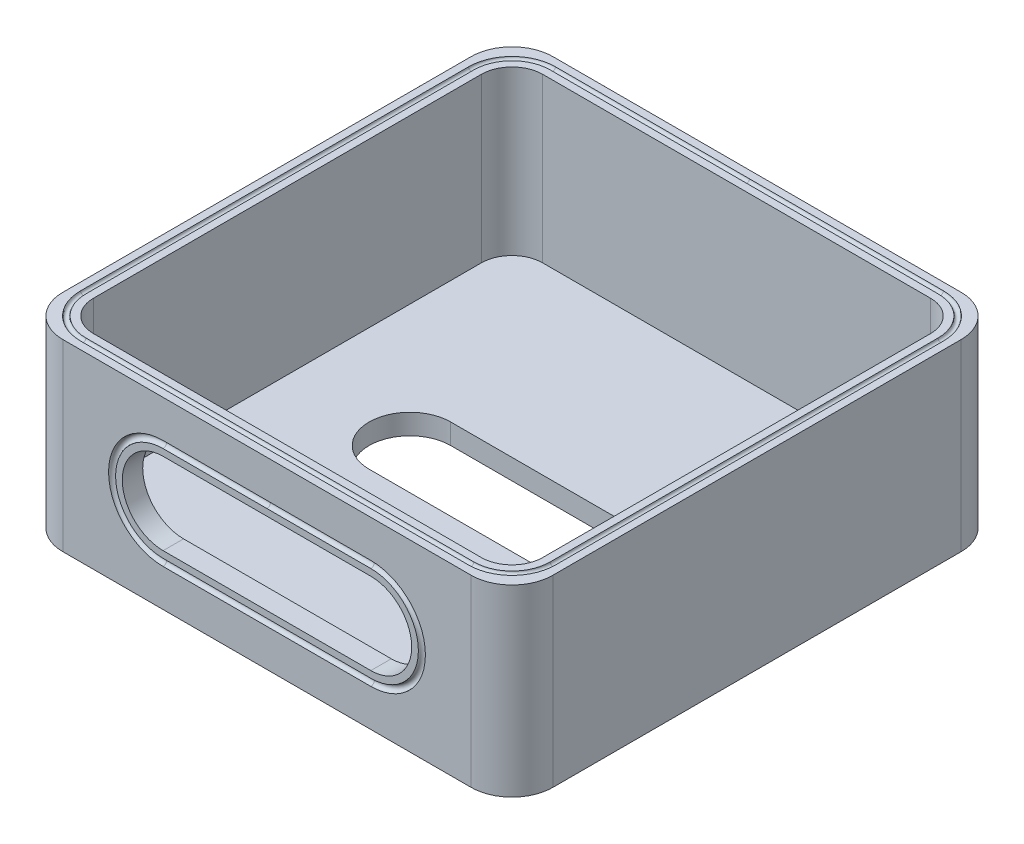
SolidWorks part; units mm, degrees
ref_plane "Front Plane" through (0, 0, 0) normal (0, 0, 1) x (1, 0, 0)
ref_plane "Top Plane" through (0, 0, 0) normal (0, 1, 0) x (1, 0, 0)
ref_plane "Right Plane" through (0, 0, 0) normal (1, 0, 0) x (0, 0, -1)
sketch "Sketch1" plane through (0, 0, 0) normal (0, 1, 0) x (1, 0, 0)
  line L0 (0, -152.4) -> (0, 152.4) construction
  line L1 (-152.4, -152.4) -> (152.4, -152.4)
  line L2 (-152.4, -152.4) -> (-152.4, 152.4)
  line L3 (-152.4, 152.4) -> (152.4, 152.4)
  line L4 (152.4, -152.4) -> (152.4, 152.4)
  line L5 (-152.4, -152.4) -> (152.4, 152.4) construction
  line L6 (-152.4, 152.4) -> (152.4, -152.4) construction
  line L7 (-152.4, 0) -> (152.4, 0) construction
  line L16 (0, -63.5) -> (0, 63.5) construction
  line L28 (-139.7, 139.7) -> (139.7, 139.7)
  line L29 (139.7, -139.7) -> (139.7, 139.7)
  line L30 (-139.7, -139.7) -> (139.7, -139.7)
  line L31 (-139.7, -139.7) -> (-139.7, 139.7)
  point P0 (0, 0)
  point P10 (0, 0)
  point P11 (0, 0)
  point P13 (-120.65, -184.15)
  point P26 (127, 190.5)
  point P27 (-127, 152.4)
  point P28 (-120.65, 184.15)
  dimension "12" = 304.8
  dimension "D2" = 304.8
  dimension "D6" = 12.7
extrude "Boss-Extrude1" add sketch "Sketch1" along normal blind 114.3
shell "Shell1" thickness 12.7
sketch "Sketch2" plane through (0, 0, 152.4) normal (0, 0, 1) x (1, 0, 0)
  line L0 (-64.6, 57.15) -> (64.6, 57.15) construction
  line L1 (-64.6, 82.55) -> (64.6, 82.55)
  line L2 (-64.6, 31.75) -> (64.6, 31.75)
  line L5 (-64.6, 88.9) -> (64.6, 88.9)
  line L6 (-64.6, 25.4) -> (64.6, 25.4)
  line L7 (0, 0) -> (0, 114.3) construction
  line L10 (-152.4, 114.3) -> (152.4, 114.3) construction
  arc A0 (-64.6, 82.55) -> (-64.6, 31.75) centre (-64.6, 57.15) ccw
  arc A1 (64.6, 31.75) -> (64.6, 82.55) centre (64.6, 57.15) ccw
  arc A2 (64.6, 25.4) -> (64.6, 88.9) centre (64.6, 57.15) ccw
  arc A3 (-64.6, 88.9) -> (-64.6, 25.4) centre (-64.6, 57.15) ccw
  point P2 (0, 57.15)
  point P16 (90, 57.15)
  point P17 (-90, 57.15)
  dimension "D1" = 50.8
  dimension "D2" = 180
  dimension "D3" = 6.35
extrude "Cut-Extrude1" cut sketch "Sketch2" against normal mid plane 43.02
sketch "Sketch9" plane through (0, 0, 152.4) normal (0, 0, 1) x (1, 0, 0)
  line L0 (64.6, 82.55) -> (-64.6, 82.55) construction
  line L1 (64.6, 31.75) -> (-64.6, 31.75) construction
  line L2 (64.6, 82.55) -> (-64.6, 82.55) construction
  line L3 (64.6, 31.75) -> (-64.6, 31.75) construction
  line L4 (64.6, 88.9) -> (-64.6, 88.9)
  line L5 (64.6, 25.4) -> (-64.6, 25.4)
  arc A0 (-64.6, 82.55) -> (-64.6, 31.75) centre (-64.6, 57.15) ccw construction
  arc A1 (64.6, 31.75) -> (64.6, 82.55) centre (64.6, 57.15) ccw construction
  arc A2 (-64.6, 82.55) -> (-64.6, 31.75) centre (-64.6, 57.15) ccw construction
  arc A3 (64.6, 31.75) -> (64.6, 82.55) centre (64.6, 57.15) ccw construction
  arc A4 (-64.6, 88.9) -> (-64.6, 25.4) centre (-64.6, 57.15) ccw
  arc A5 (64.6, 25.4) -> (64.6, 88.9) centre (64.6, 57.15) ccw
  dimension "D1" = 6.35
sketch "Sketch10" plane through (0, 0, 0) normal (1, 0, 0) x (0, 0, -1)
  circle A0 centre (-152.4, 88.9) radius 2.1844
  dimension "D1" = 4.3688
sweep "Cut-Sweep1" cut profiles "Sketch10" path "Sketch9"
sketch "Sketch13" plane through (0, 0, 0) normal (0, -1, 0) x (1, 0, 0)
  line L0 (0, 25.4) -> (0, -25.4) construction
  line L1 (-63.5, -25.4) -> (63.5, -25.4)
  line L2 (-63.5, -25.4) -> (-63.5, 25.4) construction
  line L3 (-63.5, 25.4) -> (63.5, 25.4)
  line L4 (63.5, -25.4) -> (63.5, 25.4) construction
  line L5 (-63.5, -25.4) -> (63.5, 25.4) construction
  line L6 (-63.5, 25.4) -> (63.5, -25.4) construction
  arc A0 (-63.5, 25.4) -> (-63.5, -25.4) centre (-63.5, 0) ccw
  arc A1 (63.5, 25.4) -> (63.5, -25.4) centre (63.5, 0) cw
  point P0 (0, 0)
  point P10 (0, 0)
  dimension "D1" = 127
  dimension "D2" = 50.8
extrude "Cut-Extrude5" cut sketch "Sketch13" against normal through all
sketch "Sketch14" plane through (0, 0, 0) normal (0, -1, 0) x (1, 0, 0)
  line L4 (63.5, 33.02) -> (-63.5, 33.02)
  line L5 (-63.5, -33.02) -> (63.5, -33.02)
  line L6 (63.5, 33.02) -> (-63.5, 33.02)
  line L7 (-63.5, -33.02) -> (63.5, -33.02)
  arc A4 (-63.5, 33.02) -> (-63.5, -33.02) centre (-63.5, 0) ccw
  arc A5 (63.5, -33.02) -> (63.5, 33.02) centre (63.5, 0) ccw
  arc A6 (-63.5, 33.02) -> (-63.5, -33.02) centre (-63.5, 0) ccw
  arc A7 (63.5, -33.02) -> (63.5, 33.02) centre (63.5, 0) ccw
  dimension "D1" = 7.62
sketch "Sketch16" plane through (0, 0, 0) normal (1, 0, 0) x (0, 0, -1)
  circle A0 centre (33.02, 0) radius 1.651
  dimension "D1" = 3.302
sweep "Cut-Sweep2" cut profiles "Sketch16" path "Sketch14"
sketch "Sketch17" plane through (0, 0, 0) normal (0, -1, 0) x (1, 0, 0)
  line L0 (-94.869, 0) -> (94.869, 0) construction
  line L9 (0, 0) -> (0, 40.259) construction
  line L12 (-63.5, -40.259) -> (0, -40.259)
  line L13 (0, -40.259) -> (63.5, -40.259)
  line L14 (63.5, 40.259) -> (-63.5, 40.259)
  line L15 (-63.5, -40.259) -> (0, -40.259) construction
  line L16 (0, -40.259) -> (63.5, -40.259) construction
  line L17 (63.5, 40.259) -> (-63.5, 40.259) construction
  arc A0 (-63.5, 31.369) -> (-63.5, -31.369) centre (-63.5, 0) ccw construction
  arc A1 (63.5, -31.369) -> (63.5, 31.369) centre (63.5, 0) ccw construction
  circle A8 centre (63.5, 40.259) radius 2.5527
  circle A9 centre (38.1, 40.259) radius 2.5527
  arc A10 (63.5, -40.259) -> (63.5, 40.259) centre (63.5, 0) ccw
  arc A11 (-63.5, 40.259) -> (-63.5, -40.259) centre (-63.5, 0) ccw
  arc A12 (63.5, -40.259) -> (63.5, 40.259) centre (63.5, 0) ccw construction
  arc A13 (-63.5, 40.259) -> (-63.5, -40.259) centre (-63.5, 0) ccw construction
  circle A14 centre (12.7, 40.259) radius 2.5527
  circle A15 centre (-12.7, 40.259) radius 2.5527
  circle A16 centre (-38.1, 40.259) radius 2.5527
  circle A17 centre (-63.5, 40.259) radius 2.5527
  circle A18 centre (83.6295, 34.8653) radius 2.5527
  circle A19 centre (98.3653, 20.1295) radius 2.5527
  circle A20 centre (103.759, 0) radius 2.5527
  circle A21 centre (-103.759, 0) radius 2.5527
  circle A22 centre (-98.3653, 20.1295) radius 2.5527
  circle A23 centre (-83.6295, 34.8653) radius 2.5527
  circle A24 centre (98.3653, -20.1295) radius 2.5527
  circle A25 centre (83.6295, -34.8653) radius 2.5527
  circle A26 centre (63.5, -40.259) radius 2.5527
  circle A27 centre (38.1, -40.259) radius 2.5527
  circle A28 centre (12.7, -40.259) radius 2.5527
  circle A29 centre (-12.7, -40.259) radius 2.5527
  circle A30 centre (-38.1, -40.259) radius 2.5527
  circle A31 centre (-63.5, -40.259) radius 2.5527
  circle A32 centre (-83.6295, -34.8653) radius 2.5527
  circle A33 centre (-98.3653, -20.1295) radius 2.5527
  point P31 (63.5, 0)
  dimension "D2" = 5.1054
  dimension "D1" = 8.89
  dimension "D3" = 6
  dimension "D4" = 4
extrude "Cut-Extrude6" cut sketch "Sketch17" against normal blind 6.35
fillet "Fillet2" radius 19.05 4 edges at (139.7, 63.5, -139.7) (-139.7, 63.5, -139.7) (-139.7, 63.5, 139.7) (139.7, 63.5, 139.7)
sketch "Sketch20" plane through (0, 114.3, 0) normal (0, 1, 0) x (1, 0, 0)
  line L8 (-120.65, -146.05) -> (120.65, -146.05)
  line L9 (146.05, -120.65) -> (146.05, 120.65)
  line L10 (120.65, 146.05) -> (-120.65, 146.05)
  line L11 (-146.05, 120.65) -> (-146.05, -120.65)
  line L12 (-120.65, -146.05) -> (120.65, -146.05)
  line L13 (146.05, -120.65) -> (146.05, 120.65)
  line L14 (120.65, 146.05) -> (-120.65, 146.05)
  line L15 (-146.05, 120.65) -> (-146.05, -120.65)
  arc A8 (-146.05, -120.65) -> (-120.65, -146.05) centre (-120.65, -120.65) ccw
  arc A9 (120.65, -146.05) -> (146.05, -120.65) centre (120.65, -120.65) ccw
  arc A10 (146.05, 120.65) -> (120.65, 146.05) centre (120.65, 120.65) ccw
  arc A11 (-120.65, 146.05) -> (-146.05, 120.65) centre (-120.65, 120.65) ccw
  arc A12 (-146.05, -120.65) -> (-120.65, -146.05) centre (-120.65, -120.65) ccw
  arc A13 (120.65, -146.05) -> (146.05, -120.65) centre (120.65, -120.65) ccw
  arc A14 (146.05, 120.65) -> (120.65, 146.05) centre (120.65, 120.65) ccw
  arc A15 (-120.65, 146.05) -> (-146.05, 120.65) centre (-120.65, 120.65) ccw
  dimension "D1" = 6.35
sketch "Sketch21" plane through (0, 0, 0) normal (1, 0, 0) x (0, 0, -1)
  circle A0 centre (146.05, 114.3) radius 1.651
  dimension "D1" = 3.302
sweep "Cut-Sweep4" cut profiles "Sketch21" path "Sketch20"
fillet "Fillet3" radius 25.4 4 edges at (-152.4, 57.15, -152.4) (-152.4, 57.15, 152.4) (152.4, 57.15, 152.4) (152.4, 57.15, -152.4)
